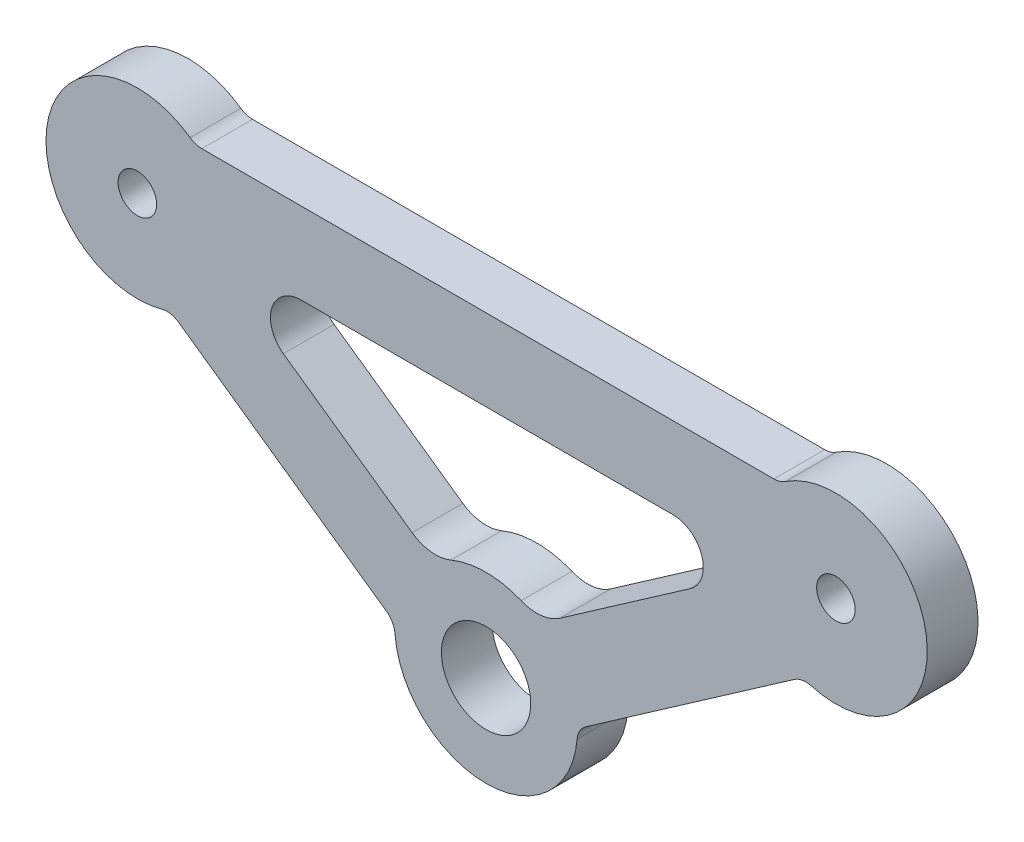
SolidWorks part; units mm, degrees
ref_plane "Plan de face" through (0, 0, 0) normal (0, 0, 1) x (1, 0, 0)
ref_plane "Plan de dessus" through (0, 0, 0) normal (0, 1, 0) x (1, 0, 0)
ref_plane "Plan de droite" through (0, 0, 0) normal (1, 0, 0) x (0, 0, -1)
sketch "Esquisse1" plane through (0, 0, 0) normal (0, 0, 1) x (1, 0, 0)
  line L0 (-18.2885, 11.0474) -> (18.1737, 11.0474)
  line L1 (-7.3443, -3.3282) -> (-20.0223, 5.5941)
  line L2 (19.9445, 5.5184) -> (7.2241, -3.3434)
  line L3 (30.3001, 2.9689) -> (9.763, -11.3385)
  line L4 (-9.8742, -11.2916) -> (-30.3428, 3.1135)
  line L5 (-28.0583, 19.0708) -> (28.2999, 19.0708)
  line L6 (-0.0574, 11.0474) -> (-0.0574, -12.0862) construction
  arc A0 (-18.2885, 11.0474) -> (-20.0223, 5.5941) centre (-18.2957, 8.0474) ccw
  arc A1 (-7.3443, -3.3282) -> (-3.5254, -3.7584) centre (-5.0422, -0.0571) ccw
  arc A2 (3.4032, -3.7553) -> (-3.5254, -3.7584) centre (-0.0574, -12.0862) ccw
  arc A3 (3.4032, -3.7553) -> (7.2241, -3.3434) centre (4.9376, -0.0613) ccw
  arc A4 (19.9445, 5.5184) -> (18.1737, 11.0474) centre (18.3379, 8.0519) ccw
  circle A5 centre (-34.4043, 12.0859) radius 1.9
  arc A6 (31.9817, 3.2541) -> (29.4676, 19.4471) centre (34.4043, 11.9219) ccw
  arc A8 (28.2999, 19.0708) -> (29.4676, 19.4471) centre (28.2999, 21.0708) ccw
  arc A9 (31.9817, 3.2541) -> (30.3001, 2.9689) centre (31.4433, 1.3279) ccw
  arc A10 (-9.0311, -12.7743) -> (8.9129, -12.8171) centre (-0.0574, -12.0862) ccw
  arc A12 (9.763, -11.3385) -> (8.9129, -12.8171) centre (10.9062, -12.9795) ccw
  arc A13 (-9.0311, -12.7743) -> (-9.8742, -11.2916) centre (-11.0252, -12.9272) ccw
  arc A15 (-29.2121, 19.4372) -> (-32.023, 3.4066) centre (-34.4043, 12.0859) ccw
  arc A16 (-30.3428, 3.1135) -> (-32.023, 3.4066) centre (-31.4939, 1.4779) ccw
  arc A17 (-29.2121, 19.4372) -> (-28.0583, 19.0708) centre (-28.0583, 21.0708) ccw
  circle A18 centre (34.4043, 11.9219) radius 1.9
  circle A19 centre (-0.0574, -12.0862) radius 4.4
  dimension "D1" = 3.8
  dimension "D2" = 2
  dimension "D3" = 9
  dimension "D4" = 9
  dimension "D5" = 9
  dimension "D6" = 2
  dimension "D7" = 2
extrude "Boss.-Extru.1" add sketch "Esquisse1" along normal blind 5
